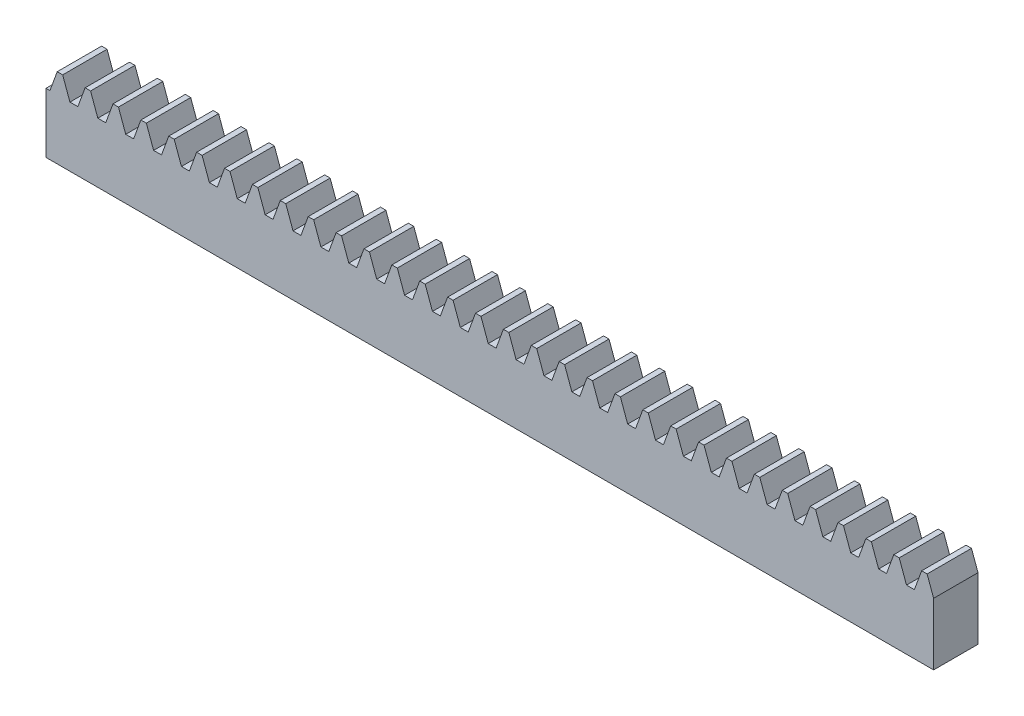
SolidWorks part; units mm, degrees
extrude "Blank" add sketch "BlankSke" against normal blind 5
sketch "BlankSke" plane through (0, 0, 0) normal (0, 0, 1) x (1, 0, 0)
  line L1 (0, 0) -> (100, 0)
  line L2 (0, 0) -> (0, 9)
  line L3 (0, 9) -> (100, 9)
  line L4 (100, 0) -> (100, 9)
  dimension "Length" = 100
  dimension "Blank_height" = 9
ref_plane "Plane1" through (0, 0, 0) normal (0, 0, 1) x (1, 0, 0)
ref_plane "Plane2" through (0, 0, 0) normal (0, 1, 0) x (1, 0, 0)
ref_plane "Plane3" through (0, 0, 0) normal (1, 0, 0) x (0, 0, -1)
sketch "HoldingSke" plane through (0, 0, 0) normal (0, 1, 0) x (1, 0, 0)
  line L0 (0, 0) -> (0.1392, 0.9903)
  line L1 (-15, 0) -> (100, 0) construction
  line L2 (0, 0) -> (-2.1039, 2.3779)
  line L3 (0, 0) -> (-11.863, 4.5341)
  line L4 (0, 0) -> (7.2428, 4.7035)
  line L5 (0, 0) -> (-23.7986, -8.8762)
  line L6 (0, 0) -> (-10.5278, -7.1032)
  line L9 (-71.009, 38.7566) -> (22.9603, 72.9586)
  line L10 (-76.2, 3.3779) -> (-68.2, 3.3779)
  line L11 (0, 0) -> (-5, 0)
  line L12 (-76.2, 101.6) -> (-76.162, 101.6)
  line L13 (24.9733, 27.94) -> (52.9518, 28.4284)
  line L14 (24.9733, 27.94) -> (24.9743, 27.94)
  line L15 (24.9733, 27.94) -> (100.4006, 29.5858)
  circle A0 centre (0, 0) radius 19.05
  circle A1 centre (0, 0) radius 4
  circle A2 centre (0, 0) radius 12.7
  dimension "MPH" = 8
  dimension "Diameter" = 38.1
  dimension "Num_teeth" = 33
  dimension "Pitch" = 1
  dimension "Show_teeth" = 998
  dimension "Thickness" = 12.7
  dimension "Ap" = 20
  dimension "Pitch_height" = 8
  dimension "Width" = 5
  dimension "Backlash" = 0.038
  dimension "Addendum_fac" = 1
  dimension "Dedendum_fac" = 1.25
  dimension "Clearance_fac" = 0.25
  dimension "Dedendum_add" = 0.001
  dimension "Length" = 100
  dimension "Module" = 1
sketch "TooCutSkeIll" plane through (0, 0, 0) normal (0, 0, 1) x (1, 0, 0)
  line L0 (-1.2538, 8.9737) -> (-0.5045, 6.9152)
  line L1 (-0.2687, 6.75) -> (0.2687, 6.75)
  line L2 (0.5045, 6.9152) -> (1.2538, 8.9737)
  line L3 (100, 9) -> (0, 9) construction
  line L4 (0, 0) -> (0, 64.897) construction
  line L5 (-13.208, 8) -> (12.954, 8) construction
  line L6 (0, 0) -> (100, 0) construction
  line L7 (0.8994, 8) -> (0.8994, 48.7463) construction
  line L8 (-0.8994, 8) -> (-0.8994, 48.7463) construction
  line L9 (1.2914, 9) -> (1.2914, 9.0254)
  line L10 (-1.2914, 9) -> (-1.2914, 9.0254)
  line L11 (-1.2914, 9.0254) -> (1.2914, 9.0254)
  arc A0 (0.2687, 6.75) -> (0.5045, 6.9152) centre (0.2687, 7.001) ccw
  arc A1 (-0.5045, 6.9152) -> (-0.2687, 6.75) centre (-0.2687, 7.001) ccw
  arc A2 (1.2914, 9) -> (1.2538, 8.9737) centre (1.2914, 8.96) ccw
  arc A3 (-1.2538, 8.9737) -> (-1.2914, 9) centre (-1.2914, 8.96) ccw
  dimension "Pitch_height" = 8
  dimension "Addendum_plus" = 1.0254
  dimension "Pressure_angle" = 20
  dimension "Gap_width" = 1.7988
  dimension "Dedendum" = 1.25
extrude "ToothCutIll" [suppressed] cut sketch "TooCutSkeIll" against normal through all
sketch "TooCutSkeSim" plane through (0, 0, 0) normal (0, 0, 1) x (1, 0, 0)
  line L0 (0.4444, 6.75) -> (-0.4444, 6.75)
  line L1 (1.2726, 9.0254) -> (0.4444, 6.75)
  line L2 (0, 17.4625) -> (0, 53.467) construction
  line L3 (1.2726, 9.0254) -> (-1.2726, 9.0254)
  line L6 (-1.2726, 9.0254) -> (-0.4444, 6.75)
  line L9 (-0.8994, 8) -> (0.8994, 8) construction
  line L10 (0, 0) -> (100, 0) construction
  line L11 (0.8994, 8) -> (0.8994, 53.467) construction
  line L12 (-0.8994, 8) -> (-0.8994, 53.467) construction
  dimension "Pitch_height" = 8
  dimension "Addendum_plus" = 1.0254
  dimension "Pressure_angle" = 20
  dimension "Gap_width" = 1.7988
  dimension "Dedendum" = 1.25
extrude "ToothCutSim" cut sketch "TooCutSkeSim" against normal through all
pattern_linear "TeethCuts" count 32 spacing 3.1416 along (1, 0, 0) of "ToothCutIll", "ToothCutSim"
equation "' \"Module@HoldingSke\" = 6.35"
equation "' \"Num_teeth@HoldingSke\" = 12"
equation "' \"Ap@HoldingSke\" =  20"
equation "' \"Ap@HoldingSke\" = 20"
equation "' \"Width@HoldingSke\" = 0.25 * 25.4"
equation "' \"Show_teeth@HoldingSke\" = 500"
equation "' \"Backlash@HoldingSke\" = 0.009 * 25.4"
equation "' \"Addendum_fac@HoldingSke\" = 1.0"
equation "' \"Dedendum_fac@HoldingSke\" = 1.25"
equation "' \"Dedendum_add@HoldingSke\" = 0.00005 * 25.4"
equation "' \"Clearance_fac@HoldingSke\" = 0.25"
equation "' \"Pitch_height@HoldingSke\" = 1 * 25.4"
equation "' \"Length@HoldingSke\" = 4.71 * 25.4"
equation "\"Pitch@HoldingSke\" = 1 / \"Module@HoldingSke\""
equation "\"MPH@HoldingSke\" = \"Dedendum_fac@HoldingSke\" / \"Pitch@HoldingSke\" + 2 * \"Dedendum_add@HoldingSke\" + 0.002 * 25.4"
equation "\"MPH@HoldingSke\" = ((sgn( \"MPH@HoldingSke\" - \"Pitch_height@HoldingSke\")+1)*( \"MPH@HoldingSke\" - \"Pitch_height@HoldingSke\"))/2 + \"Pitch_height@HoldingSke\""
equation "\"Blank_height@BlankSke\" = \"Pitch_height@HoldingSke\" + \"Addendum_fac@HoldingSke\"  / \"Pitch@HoldingSke\" "
equation "\"Length@BlankSke\" =  \"Length@HoldingSke\""
equation "\"Face_width@Blank\" = \"Width@HoldingSke\""
equation "\"Pressure_angle@TooCutSkeIll\" = \"Ap@HoldingSke\""
equation "\"Addendum_plus@TooCutSkeIll\" =  \"Addendum_fac@HoldingSke\"  / \"Pitch@HoldingSke\" + 0.001 *25.4"
equation "\"Dedendum@TooCutSkeIll\" = \"Dedendum_fac@HoldingSke\"  / \"Pitch@HoldingSke\""
equation "\"Pitch_height@TooCutSkeIll\" =  \"MPH@HoldingSke\""
equation "\"Gap_width@TooCutSkeIll\" = 3.14159265 / 2 / \"Pitch@HoldingSke\" + 6 * \"Backlash@HoldingSke\""
equation "\"Pressure_angle@TooCutSkeSim\" = \"Ap@HoldingSke\""
equation "\"Addendum_plus@TooCutSkeSim\" =  \"Addendum_fac@HoldingSke\"  / \"Pitch@HoldingSke\" + 0.001 * 25.4"
equation "\"Dedendum@TooCutSkeSim\" = \"Dedendum_fac@HoldingSke\"  / \"Pitch@HoldingSke\""
equation "\"Pitch_height@TooCutSkeSim\" =  \"MPH@HoldingSke\""
equation "\"Gap_width@TooCutSkeSim\" = 3.14159265 / 2 / \"Pitch@HoldingSke\" + 6 * \"Backlash@HoldingSke\""
equation "\"Root_fillet@TooCutSkeIll\" = \"Clearance_fac@HoldingSke\" / \"Pitch@HoldingSke\" + \"Dedendum_add@HoldingSke\""
equation "\"Break_rad@TooCutSkeIll\" = 0.02 / \"Pitch@HoldingSke\" * 2"
equation "\"Linear_pitch@TeethCuts\" = 3.14159265 / \"Pitch@HoldingSke\""
equation "\"Num_teeth@HoldingSke\" = int( ( \"Length@HoldingSke\" + 0 ) / (3.14159265 / \"Pitch@HoldingSke\")) + 0.9999  + 1"
equation " \"Num_teeth@TeethCuts\" = int( \"Show_teeth@HoldingSke\" ) + 1"
equation " \"Num_teeth@TeethCuts\" = ((sgn( \"Num_teeth@TeethCuts\" - \"Num_teeth@HoldingSke\" )-1)*( \"Num_teeth@TeethCuts\" - \"Num_teeth@HoldingSke\" ))/-2+ \"Num_teeth@HoldingSke\""
equation " \"Num_teeth@TeethCuts\" = ((sgn( \"Num_teeth@TeethCuts\" - 2.0)+1)*( \"Num_teeth@TeethCuts\" - 2.0))/2 +2.0"
